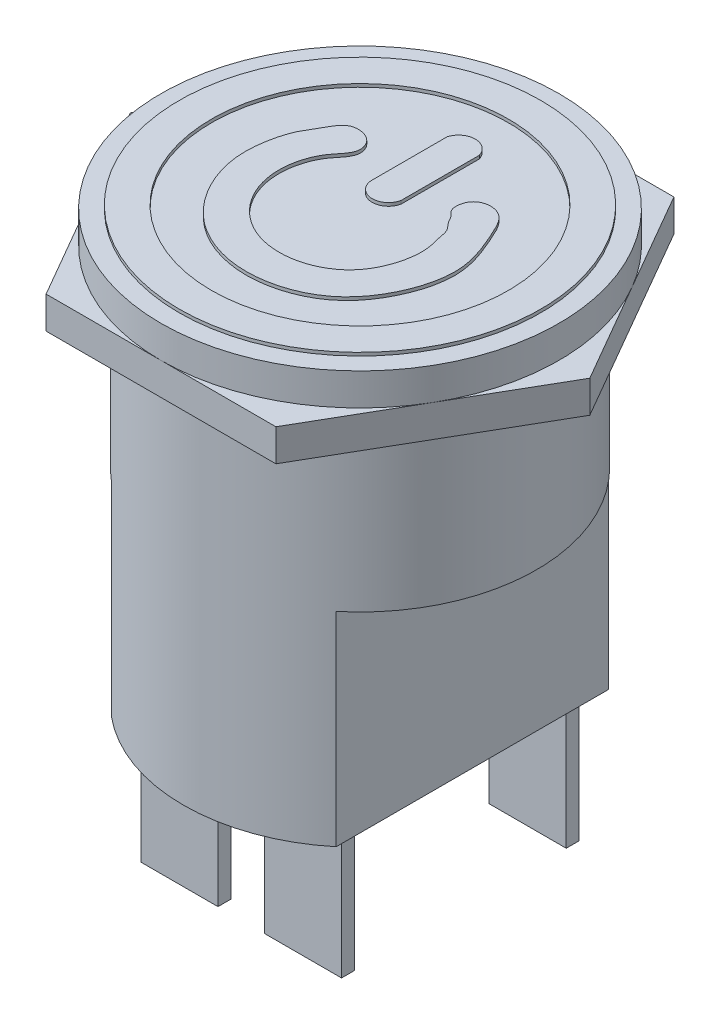
SolidWorks part; units mm, degrees
ref_plane "前视基准面" through (0, 0, 0) normal (0, 0, 1) x (1, 0, 0)
ref_plane "上视基准面" through (0, 0, 0) normal (0, 1, 0) x (1, 0, 0)
ref_plane "右视基准面" through (0, 0, 0) normal (1, 0, 0) x (0, 0, -1)
other "Configuration Table"
sketch "草图1" plane through (0, 0, 0) normal (0, 1, 0) x (1, 0, 0)
  circle A0 centre (0, 0) radius 11
  dimension "D1" = 22
extrude "凸台-拉伸1" add sketch "草图1" along normal blind 10
cosmetic thread "装饰螺纹线1" parameters "D2"=19.294
sketch "草图2" plane through (0, 10, 0) normal (0, 1, 0) x (1, 0, 0)
  line L1 (7.1591, -12.4) -> (14.3183, 0)
  line L2 (14.3183, 0) -> (7.1591, 12.4)
  line L3 (7.1591, 12.4) -> (-7.1591, 12.4)
  line L4 (-7.1591, 12.4) -> (-14.3183, 0)
  line L5 (-14.3183, 0) -> (-7.1591, -12.4)
  line L6 (-7.1591, -12.4) -> (7.1591, -12.4)
  circle A0 centre (0, 0) radius 12.4 construction
  dimension "D1" = 24.8
extrude "凸台-拉伸2" add sketch "草图2" along normal blind 2
sketch "草图3" plane through (0, 12, 0) normal (0, 1, 0) x (1, 0, 0)
  circle A0 centre (0, 0) radius 12.4
  dimension "D1" = 24.8
extrude "凸台-拉伸3" add sketch "草图3" along normal blind 2
sketch "草图5" plane through (0, 14, 0) normal (0, 1, 0) x (1, 0, 0)
  line L0 (38.3615, 137.7801) -> (236.3615, 137.7801) construction
  line L1 (-0.9531, 6.3872) -> (-0.9531, 1.6206)
  line L2 (1.0475, 6.3872) -> (1.0475, 1.5182)
  circle A0 centre (0, 0) radius 11.2646
  circle A1 centre (0, 0) radius 9.2518
  arc A2 (-0.9531, 6.3872) -> (1.0475, 6.3872) centre (0.0472, 6.0933) cw
  arc A3 (-0.9531, 1.6206) -> (1.0475, 1.5182) centre (0.0549, 1.7194) ccw
  spline S0 degree 3 poles (-3.8208, 4.0506) (-4.8275, 4.0022) (-5.3117, 2.9603) (-5.9911, 1.9492) (-6.3963, 0.5243) (-6.5374, -1.2863) (-5.8405, -3.7805) (-3.9735, -6.1245) (-1.2384, -7.1694) (1.5208, -7.1734) (4.2114, -6.0842) (6.0867, -3.4777) (6.9054, -0.3677) (5.9051, 2.0596) (5.0288, 3.9628) (3.8753, 4.0418) (3.2914, 3.6963) (3.0487, 3.142) (3.0614, 2.5264) (3.4882, 2.2346) (3.6793, 1.7694) (4.169, 1.3627) (4.2231, 0.6594) (4.5156, -0.228) (4.4613, -1.3697) (4.0794, -2.5939) (3.3033, -3.915) (1.9359, -4.8155) (0.2782, -5.1492) (-1.2197, -5.0048) (-2.8324, -4.2118) (-4.0443, -2.7358) (-4.4963, -0.9446) (-4.312, 0.5539) (-3.8246, 1.6526) (-3.2278, 2.2832) (-2.8898, 2.9399) (-3.1279, 3.6992) (-3.8208, 4.0506) (-4.8275, 4.0022) (-5.3117, 2.9603) knots -0.038485 -0.02566 -0.011428 0 0.023974 0.041554 0.066468 0.100999 0.137142 0.201932 0.251863 0.287327 0.347456 0.397065 0.454432 0.507559 0.538353 0.553212 0.562962 0.572499 0.584637 0.591443 0.598437 0.610872 0.623269 0.634066 0.660781 0.681865 0.702097 0.741217 0.764094 0.791316 0.819614 0.857638 0.888785 0.915262 0.936721 0.951197 0.961515 0.97434 0.988572 1 1.023974 1.041554 1.066468 only from (-4.5319, 3.9455) to (-4.5319, 3.9455)
extrude "凸台-拉伸4" add sketch "草图5" along normal blind 0.2 contours L1 A3 L2 A2 | S0 | A0 A1
sketch "草图6" plane through (0, 0, 0) normal (0, -1, 0) x (1, 0, 0)
  line L1 (7, -8.4853) -> (-7, -8.4853)
  line L2 (7, -8.4853) -> (7, 8.4853)
  line L3 (7, 8.4853) -> (-7, 8.4853)
  line L4 (-7, -8.4853) -> (-7, 8.4853)
  circle A1 centre (0, 0) radius 11
  circle A2 centre (0, 0) radius 11
  circle M3 centre (0, 0) radius 11
  dimension "D2" = 14
  dimension "D1" = 0
extrude "凸台-拉伸5" add sketch "草图6" along normal blind 12.7 contours L4 L1 L2 L3 | L3 M3 | L1 M3
sketch "草图7" plane through (0, -12.7, 0) normal (0, -1, 0) x (1, 0, 0)
  line L0 (-7, 0) -> (7, 0) construction
  line L1 (-7, -8.4853) -> (-7, 8.4853) construction
  line L2 (7, -8.4853) -> (7, 8.4853) construction
  line L3 (0, 11) -> (0, -11) construction
  line L4 (1.45, 6.6) -> (1.45, 7.4)
  line L5 (-1.45, 6.6) -> (-6.25, 6.6)
  line L6 (-1.45, 6.6) -> (-1.45, 7.4)
  line L7 (-1.45, 7.4) -> (-6.25, 7.4)
  line L8 (-6.25, 6.6) -> (-6.25, 7.4)
  line L9 (1.45, 7.4) -> (6.25, 7.4)
  line L10 (6.25, 6.6) -> (6.25, 7.4)
  line L11 (1.45, 6.6) -> (6.25, 6.6)
  line L12 (1.45, -6.6) -> (6.25, -6.6)
  line L13 (6.25, -6.6) -> (6.25, -7.4)
  line L14 (1.45, -7.4) -> (6.25, -7.4)
  line L15 (-6.25, -6.6) -> (-6.25, -7.4)
  line L16 (-1.45, -7.4) -> (-6.25, -7.4)
  line L17 (-1.45, -6.6) -> (-1.45, -7.4)
  line L18 (-1.45, -6.6) -> (-6.25, -6.6)
  line L19 (1.45, -6.6) -> (1.45, -7.4)
  arc A0 (7, 8.4853) -> (-7, 8.4853) centre (0, 0) ccw construction
  arc A1 (-7, -8.4853) -> (7, -8.4853) centre (0, 0) ccw construction
  point P18 (-1.45, 7)
  point P19 (-3.85, 6.6)
  dimension "D1" = 4.8
  dimension "D2" = 7
  dimension "D3" = 3.85
  dimension "D4" = 0.8
extrude "凸台-拉伸6" add sketch "草图7" along normal blind 8
